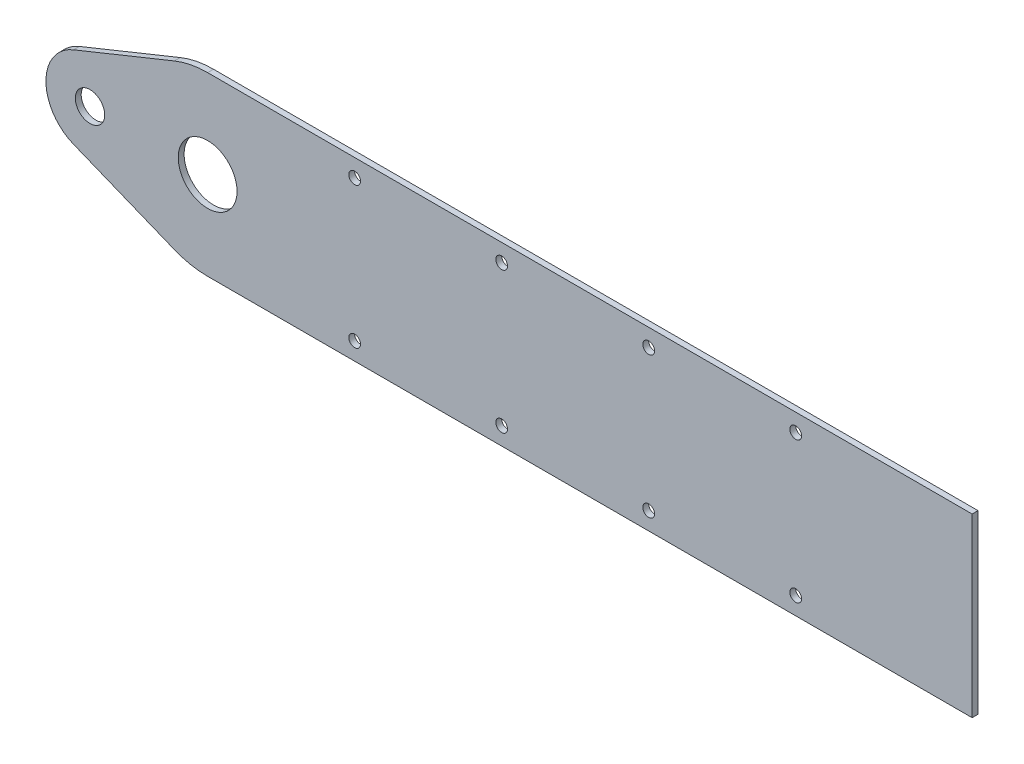
SolidWorks part; units mm, degrees
ref_plane "Спереди" through (0, 0, 0) normal (0, 0, 1) x (1, 0, 0)
ref_plane "Сверху" through (0, 0, 0) normal (0, 1, 0) x (1, 0, 0)
ref_plane "Справа" through (0, 0, 0) normal (1, 0, 0) x (0, 0, -1)
sketch "Эскиз1" plane through (0, 0, 0) normal (0, 0, 1) x (1, 0, 0)
  line L0 (-5.6443, 13.8976) -> (-22.8125, 6.9527)
  line L1 (-5.625, -13.9054) -> (-22.8125, -6.9527)
  line L6 (0, 15) -> (130, 15)
  line L8 (0, -15) -> (130, -15)
  line L9 (130, 15) -> (130, -15)
  arc A1 (-5.625, -13.9054) -> (0, -15) centre (0, 0) ccw
  circle A2 centre (-20, 0) radius 2.5
  arc A3 (-22.8125, 6.9527) -> (-22.8125, -6.9527) centre (-20, 0) ccw
  arc A4 (0, 15) -> (-5.6443, 13.8976) centre (0, 0) ccw
  circle A6 centre (0, 0) radius 5
  circle A7 centre (25, 12) radius 1
  circle A8 centre (50, 12) radius 1
  circle A9 centre (75, 12) radius 1
  circle A10 centre (100, 12) radius 1
  circle A11 centre (25, -12) radius 1
  circle A12 centre (50, -12) radius 1
  circle A13 centre (75, -12) radius 1
  circle A14 centre (100, -12) radius 1
  point P7 (0, 0)
  point P13 (0, 0)
  point P15 (0, 0)
  point P22 (0, 0)
  dimension "D1" = 20
  dimension "D2" = 10
  dimension "D3" = 5
  dimension "D4" = 15
  dimension "D5" = 7.5
  dimension "D6" = 130
  dimension "D11" = 25
  dimension "D12" = 25
  dimension "D8" = 12
  dimension "D9" = 2
  dimension "D15" = 2
  dimension "D16" = 2
  dimension "D17" = 2
  dimension "D19" = 2
  dimension "D20" = 2
  dimension "D21" = 2
  dimension "D22" = 2
  dimension "D7" = 30
  dimension "D13" = 25
  dimension "D14" = 25
  dimension "D18" = 12
extrude "Бобышка-Вытянуть1" add sketch "Эскиз1" along normal blind 1
